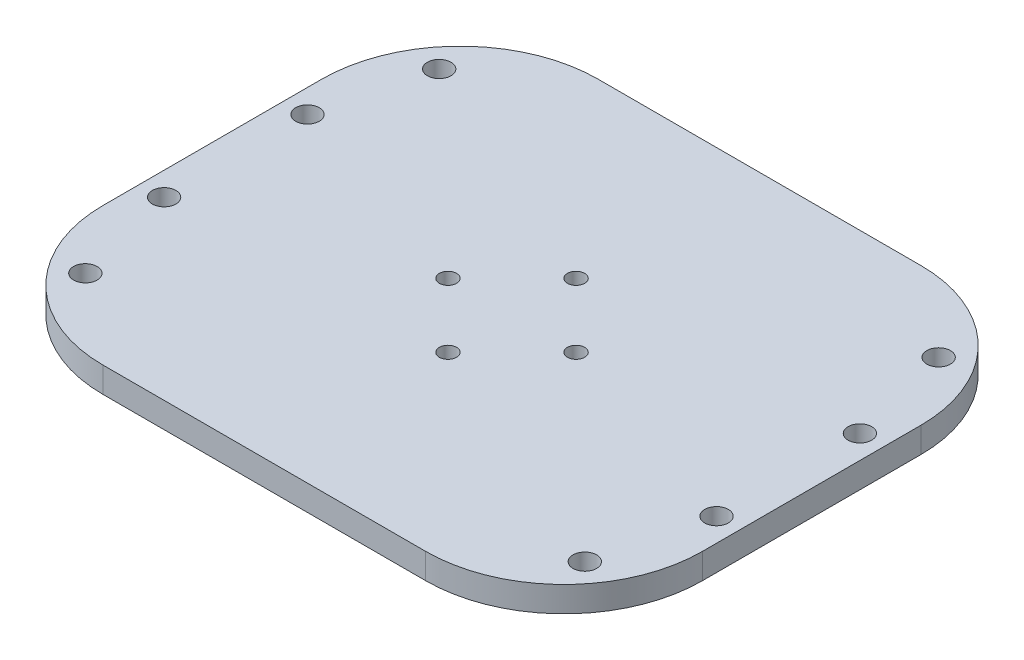
SolidWorks part; units mm, degrees
material "Oak"
ref_plane "Front Plane" through (0, 0, 0) normal (0, 0, 1) x (1, 0, 0)
ref_plane "Top Plane" through (0, 0, 0) normal (0, 1, 0) x (1, 0, 0)
ref_plane "Right Plane" through (0, 0, 0) normal (1, 0, 0) x (0, 0, -1)
sketch "Sketch1" plane through (0, 0, 0) normal (0, 1, 0) x (1, 0, 0)
  line L0 (20.1501, -30.9245) -> (-20.1501, -30.9245)
  line L1 (37.4269, -13.6477) -> (37.4269, 13.6477)
  line L2 (-37.4269, -13.6477) -> (-37.4269, 13.6477)
  line L3 (20.1501, 30.9245) -> (-20.1501, 30.9245)
  line L4 (37.4269, -30.9245) -> (-37.4269, 30.9245) construction
  line L5 (-37.4269, -30.9245) -> (37.4269, 30.9245) construction
  arc A0 (37.4269, 13.6477) -> (20.1501, 30.9245) centre (20.1501, 13.6477) ccw
  arc A1 (-20.1501, -30.9245) -> (-37.4269, -13.6477) centre (-20.1501, -13.6477) cw
  arc A2 (20.1501, -30.9245) -> (37.4269, -13.6477) centre (20.1501, -13.6477) ccw
  arc A3 (-20.1501, 30.9245) -> (-37.4269, 13.6477) centre (-20.1501, 13.6477) ccw
  point P1 (0, 0)
  dimension "D3" = 17.2768
  dimension "D1" = 74.8538
  dimension "D2" = 61.849
extrude "Boss-Extrude1" add sketch "Sketch1" along normal blind 3.175
sketch "Sketch2" plane through (0, 3.175, 0) normal (0, 1, 0) x (1, 0, 0)
  circle A0 centre (0, 0) radius 8 construction
  point P3 (-8, 0)
  point P4 (0, 8)
  point P5 (8, 0)
  point P6 (0, -8)
  dimension "D1" = 8
hole_wizard "#4 Clearance Hole1" positions "Sketch4" profile "Sketch3" hole size "#4" standard "Ansi Inch" end condition through all
sketch "Sketch4" plane through (0, 3.175, 0) normal (0, 1, 0) x (-1, 0, 0)
  point P1 (0, -8)
  point P4 (-8, 0)
  point P7 (0, 8)
  point P13 (8, 0)
sketch "Sketch3" plane through (0, 3.175, -8) normal (1, 0, 0) x (0, 0, 1)
  line L0 (0, 0) -> (0, 3.175)
  line L1 (0, 3.175) -> (1.0795, 3.175)
  line L2 (1.0795, 3.175) -> (1.0795, 0)
  line L5 (1.0795, 0) -> (0, 0)
  line L11 (0, -6.35) -> (0, 107.95) construction
  dimension "Thru Hole Dia." = 2.159
  dimension "Thru Hole Depth" = 3.175
sketch "Sketch5" plane through (0, 3.175, 0) normal (0, 1, 0) x (-1, 0, 0)
  line L0 (0, 30.9245) -> (0, -30.9245) construction
  line L1 (-20.1501, -30.9245) -> (20.1501, -30.9245) construction
  line L2 (20.1501, 30.9245) -> (-20.1501, 30.9245) construction
sketch "Sketch6" plane through (0, 3.175, 0) normal (0, 1, 0) x (-1, 0, 0)
  line L0 (-31.1912, 22.098) -> (31.1912, 22.098) construction
  line L1 (-31.1912, 22.098) -> (-31.1912, -22.098) construction
  line L2 (31.1912, 22.098) -> (31.1912, -22.098) construction
  line L3 (-31.1912, -22.098) -> (31.1912, -22.098) construction
  line L4 (-31.1912, 22.098) -> (31.1912, -22.098) construction
  line L5 (31.1912, 22.098) -> (-31.1912, -22.098) construction
  line L6 (-34.5, 8.9535) -> (34.5, 8.9535) construction
  line L7 (-34.5, 8.9535) -> (-34.5, -8.9535) construction
  line L8 (34.5, 8.9535) -> (34.5, -8.9535) construction
  line L9 (-34.5, -8.9535) -> (34.5, -8.9535) construction
  line L10 (-34.5, 8.9535) -> (34.5, -8.9535) construction
  line L11 (34.5, 8.9535) -> (-34.5, -8.9535) construction
  point P0 (0, 0)
  point P1 (0, 0)
  dimension "D1" = 44.196
  dimension "D2" = 62.3824
  dimension "D3" = 69
  dimension "D4" = 17.907
hole_wizard "#4 Clearance Hole2" positions "Sketch8" profile "Sketch7" hole size "#4" standard "Ansi Inch" end condition through all
sketch "Sketch8" plane through (0, 3.175, 0) normal (0, 1, 0) x (-1, 0, 0)
  point P1 (31.1912, -22.098)
  point P4 (-31.1912, -22.098)
  point P7 (-31.1912, 22.098)
  point P10 (31.1912, 22.098)
  point P92 (34.5, -8.9535)
  point P95 (34.5, 8.9535)
  point P98 (-34.5, 8.9535)
  point P101 (-34.5, -8.9535)
sketch "Sketch7" plane through (-31.1912, 3.175, -22.098) normal (1, 0, 0) x (0, 0, 1)
  line L0 (0, 0) -> (0, 3.175)
  line L1 (0, 3.175) -> (1.4732, 3.175)
  line L2 (1.4732, 3.175) -> (1.4732, 0)
  line L5 (1.4732, 0) -> (0, 0)
  line L11 (0, -6.35) -> (0, 107.95) construction
  dimension "Thru Hole Dia." = 2.9464
  dimension "Thru Hole Depth" = 3.175
